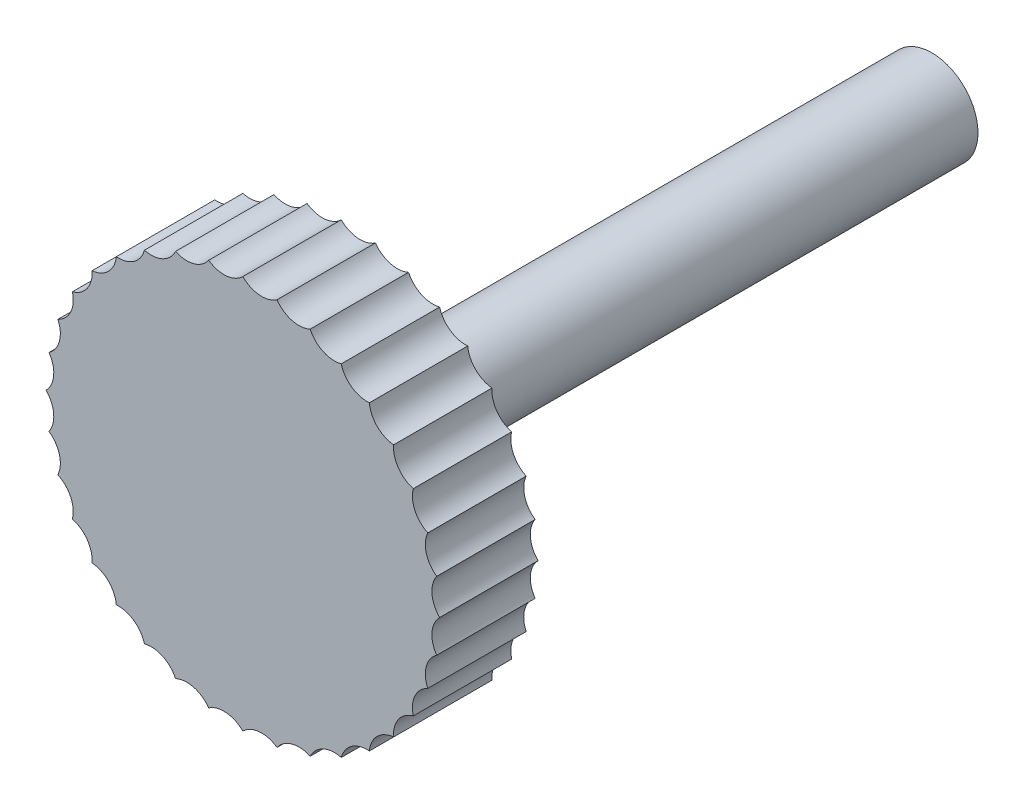
SolidWorks part; units mm, degrees
ref_plane "Ebene vorne" through (0, 0, 0) normal (0, 0, 1) x (1, 0, 0)
ref_plane "Ebene oben" through (0, 0, 0) normal (0, 1, 0) x (1, 0, 0)
ref_plane "Ebene rechts" through (0, 0, 0) normal (1, 0, 0) x (0, 0, -1)
sketch "Skizze1" plane through (0, 0, 0) normal (0, 0, 1) x (1, 0, 0)
  circle A0 centre (0, 0) radius 2.35
  dimension "D1" = 4.7
extrude "Aufsatz-Linear austragen1" add sketch "Skizze1" along normal blind 30
sketch "Skizze2" [suppressed] plane through (0, 0, 0) normal (0, 0, 1) x (1, 0, 0)
  circle A0 centre (0, 0) radius 5.023
extrude "Aufsatz-Linear austragen2" [suppressed] add sketch "Skizze2" along normal blind 4
sketch "Skizze3" [suppressed] plane through (0, 0, 0) normal (0, 0, -1) x (-1, 0, 0)
  circle A0 centre (0, 0) radius 1.55
  dimension "D1" = 3.1
extrude "Schnitt-Linear austragen1" [suppressed] cut sketch "Skizze3" against normal blind 6
sketch "Skizze4" plane through (0, 0, 0) normal (0, 0, -1) x (-1, 0, 0)
  circle A0 centre (0, 0) radius 1.55
  dimension "D1" = 3.1
extrude "Schnitt-Linear austragen2" cut sketch "Skizze4" against normal blind 6
sketch "Skizze5" plane through (0, 0, 30) normal (0, 0, 1) x (1, 0, 0)
  circle A0 centre (0, 0) radius 10
  dimension "D1" = 20
extrude "Aufsatz-Linear austragen3" add sketch "Skizze5" along normal blind 5
sketch "Skizze6" plane through (0, 0, 35) normal (0, 0, 1) x (1, 0, 0)
  line L0 (0, 0) -> (0, 10.4808) construction
  line L1 (0, 0) -> (1.9557, 11.0911) construction
  arc A0 (0, 10) -> (1.7365, 9.8481) centre (0.9593, 10.9651) ccw
  circle A1 centre (0, 0) radius 10 construction
  arc A2 (1.7365, 9.8481) -> (3.4202, 9.3969) centre (2.8488, 10.6319) ccw
  arc A3 (3.4202, 9.3969) -> (5, 8.6603) centre (4.6518, 9.9757) ccw
  arc A4 (5, 8.6603) -> (6.4279, 7.6604) centre (6.3134, 9.0164) ccw
  arc A5 (6.4279, 7.6604) -> (7.6604, 6.4279) centre (7.7831, 7.7831) ccw
  arc A6 (7.6604, 6.4279) -> (8.6603, 5) centre (9.0164, 6.3134) ccw
  arc A7 (8.6603, 5) -> (9.3969, 3.4202) centre (9.9757, 4.6518) ccw
  arc A8 (9.3969, 3.4202) -> (9.8481, 1.7365) centre (10.6319, 2.8488) ccw
  arc A9 (9.8481, 1.7365) -> (10, 0) centre (10.9651, 0.9593) ccw
  arc A10 (10, 0) -> (9.8481, -1.7365) centre (10.9651, -0.9593) ccw
  arc A11 (9.8481, -1.7365) -> (9.3969, -3.4202) centre (10.6319, -2.8488) ccw
  arc A12 (9.3969, -3.4202) -> (8.6603, -5) centre (9.9757, -4.6518) ccw
  arc A13 (8.6603, -5) -> (7.6604, -6.4279) centre (9.0164, -6.3134) ccw
  arc A14 (7.6604, -6.4279) -> (6.4279, -7.6604) centre (7.7831, -7.7831) ccw
  arc A15 (6.4279, -7.6604) -> (5, -8.6603) centre (6.3134, -9.0164) ccw
  arc A16 (5, -8.6603) -> (3.4202, -9.3969) centre (4.6518, -9.9757) ccw
  arc A17 (3.4202, -9.3969) -> (1.7365, -9.8481) centre (2.8488, -10.6319) ccw
  arc A18 (1.7365, -9.8481) -> (0, -10) centre (0.9593, -10.9651) ccw
  arc A19 (0, -10) -> (-1.7365, -9.8481) centre (-0.9593, -10.9651) ccw
  arc A20 (-1.7365, -9.8481) -> (-3.4202, -9.3969) centre (-2.8488, -10.6319) ccw
  arc A21 (-3.4202, -9.3969) -> (-5, -8.6603) centre (-4.6518, -9.9757) ccw
  arc A22 (-5, -8.6603) -> (-6.4279, -7.6604) centre (-6.3134, -9.0164) ccw
  arc A23 (-6.4279, -7.6604) -> (-7.6604, -6.4279) centre (-7.7831, -7.7831) ccw
  arc A24 (-7.6604, -6.4279) -> (-8.6603, -5) centre (-9.0164, -6.3134) ccw
  arc A25 (-8.6603, -5) -> (-9.3969, -3.4202) centre (-9.9757, -4.6518) ccw
  arc A26 (-9.3969, -3.4202) -> (-9.8481, -1.7365) centre (-10.6319, -2.8488) ccw
  arc A27 (-9.8481, -1.7365) -> (-10, 0) centre (-10.9651, -0.9593) ccw
  arc A28 (-10, 0) -> (-9.8481, 1.7365) centre (-10.9651, 0.9593) ccw
  arc A29 (-9.8481, 1.7365) -> (-9.3969, 3.4202) centre (-10.6319, 2.8488) ccw
  arc A30 (-9.3969, 3.4202) -> (-8.6603, 5) centre (-9.9757, 4.6518) ccw
  arc A31 (-8.6603, 5) -> (-7.6604, 6.4279) centre (-9.0164, 6.3134) ccw
  arc A32 (-7.6604, 6.4279) -> (-6.4279, 7.6604) centre (-7.7831, 7.7831) ccw
  arc A33 (-6.4279, 7.6604) -> (-5, 8.6603) centre (-6.3134, 9.0164) ccw
  arc A34 (-5, 8.6603) -> (-3.4202, 9.3969) centre (-4.6518, 9.9757) ccw
  arc A35 (-3.4202, 9.3969) -> (-1.7365, 9.8481) centre (-2.8488, 10.6319) ccw
  arc A36 (-1.7365, 9.8481) -> (0, 10) centre (-0.9593, 10.9651) ccw
  circle A37 centre (0, 0) radius 12.1902
  point P117 (0, 0)
  dimension "D1" = 10
  dimension "D2" = 36
extrude "Schnitt-Linear austragen3" cut sketch "Skizze6" against normal up to next
